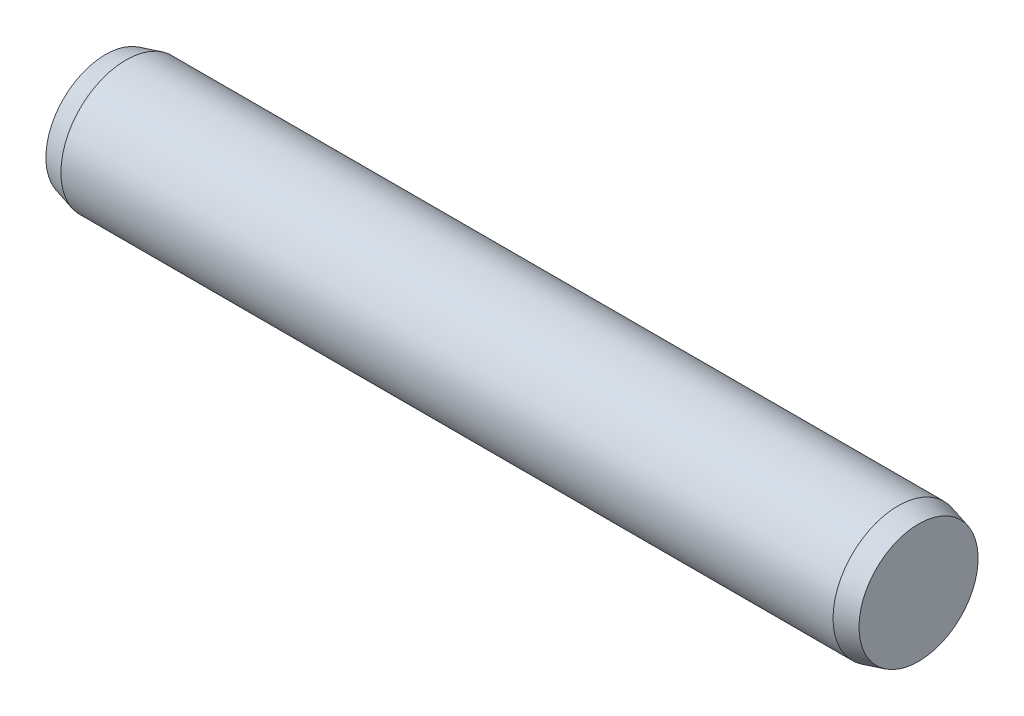
SolidWorks part; units mm, degrees
material "1.4305 (X8CrNiS18-9)"
ref_plane "正面" through (0, 0, 0) normal (0, 0, 1) x (1, 0, 0)
ref_plane "平面" through (0, 0, 0) normal (0, 1, 0) x (1, 0, 0)
ref_plane "右側面" through (0, 0, 0) normal (1, 0, 0) x (0, 0, -1)
sketch "ｽｹｯﾁ1" plane through (0, 0, 0) normal (0, 0, 1) x (1, 0, 0)
  line L0 (0, 0) -> (9067.0484, 0) construction
  line L1 (-12.5, 0) -> (-12.5, 2)
  line L2 (-12.5, 2) -> (12.5, 2)
  line L3 (12.5, 2) -> (12.5, 0)
  line L4 (12.5, 0) -> (-12.5, 0)
  point P7 (0, 0)
  dimension "D1" = 4
  dimension "D2" = 25
revolve "回転1" add sketch "ｽｹｯﾁ1" angle 360 about L0
chamfer "面取り1" distance 0.63 angle 15 2 edges at (12.5, 0, 2) (-12.5, 0, 2)
